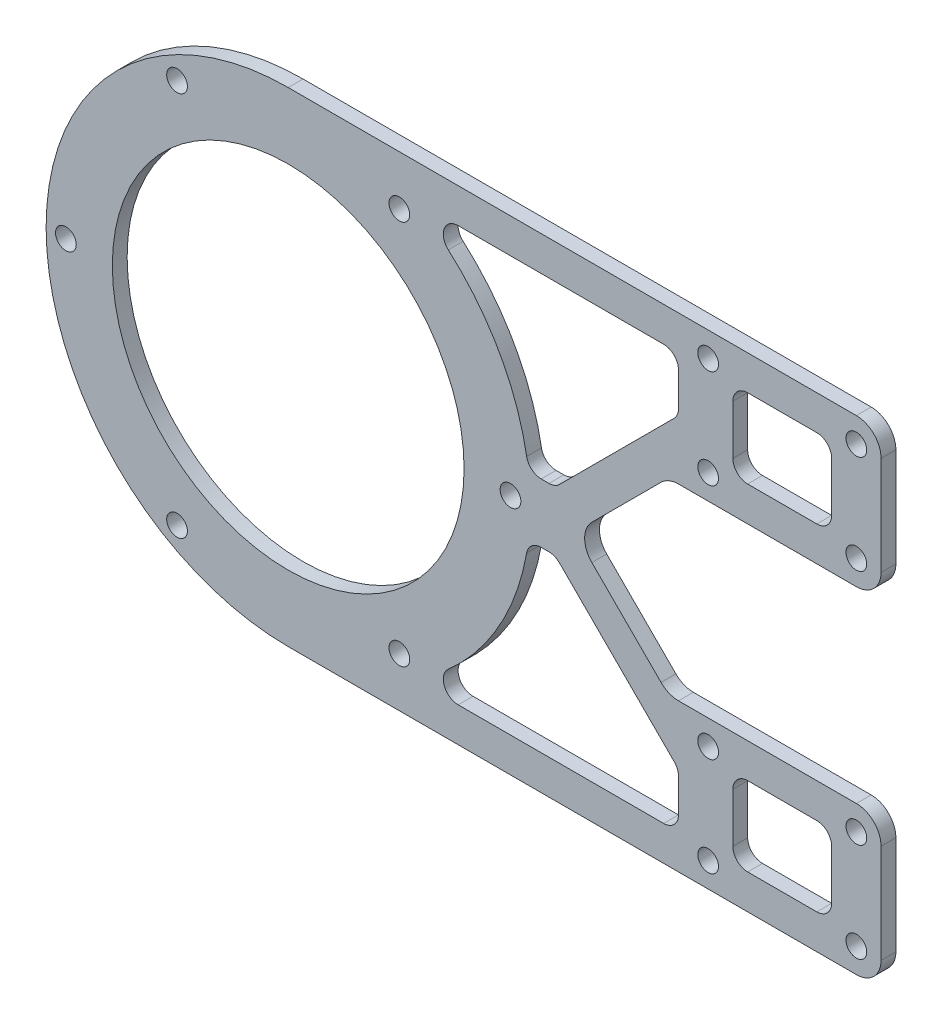
SolidWorks part; units mm, degrees
material "Thornel Mat VMA"
ref_plane "前视基准面" through (0, 0, 0) normal (0, 0, 1) x (1, 0, 0)
ref_plane "上视基准面" through (0, 0, 0) normal (0, 1, 0) x (1, 0, 0)
ref_plane "右视基准面" through (0, 0, 0) normal (1, 0, 0) x (0, 0, -1)
other "Configuration Table"
sketch "草图1" plane through (0, 0, 0) normal (0, 0, 1) x (1, 0, 0)
  line L0 (0, 49) -> (115, 49)
  line L1 (0, -49) -> (115, -49)
  line L2 (120, 44) -> (120, 24)
  line L3 (115, 19) -> (79, 19)
  line L4 (0, 0) -> (18.0163, 0) construction
  line L5 (115, -19) -> (79, -19)
  line L6 (120, -44) -> (120, -24)
  line L7 (75.4645, 17.5355) -> (61.4645, 3.5355)
  line L8 (75.4645, -17.5355) -> (61.4645, -3.5355)
  circle A0 centre (0, 0) radius 45 construction
  circle A1 centre (-45, 0) radius 2.1
  circle A2 centre (-22.5, 38.9711) radius 2.1
  circle A3 centre (22.5, 38.9711) radius 2.1
  circle A4 centre (45, 0) radius 2.1
  circle A5 centre (22.5, -38.9711) radius 2.1
  circle A6 centre (-22.5, -38.9711) radius 2.1
  circle A7 centre (0, 0) radius 35.6
  arc A8 (0, 49) -> (0, -49) centre (0, 0) ccw
  arc A9 (79, -19) -> (75.4645, -17.5355) centre (79, -14) cw
  arc A10 (79, 19) -> (75.4645, 17.5355) centre (79, 14) ccw
  arc A11 (61.4645, 3.5355) -> (61.4645, -3.5355) centre (65, 0) ccw
  arc A12 (115, -49) -> (120, -44) centre (115, -44) ccw
  arc A13 (115, -19) -> (120, -24) centre (115, -24) cw
  arc A14 (120, 24) -> (115, 19) centre (115, 24) cw
  arc A15 (115, 49) -> (120, 44) centre (115, 44) cw
  point P18 (0, 0)
  point P30 (76.9289, -19)
  point P33 (76.9289, 19)
  point P36 (57.9289, 0)
  point P39 (120, -49)
  point P42 (120, -19)
  point P45 (120, 19)
  point P48 (120, 49)
  dimension "D1" = 90
  dimension "D2" = 4.2
  dimension "D4" = 71.2
  dimension "D5" = 49
  dimension "D8" = 5
  dimension "D9" = 5
  dimension "D6" = 30
  dimension "D7" = 45
  dimension "D10" = 20
  dimension "D11" = 120
  dimension "D3" = 6
extrude "凸台-拉伸1" add sketch "草图1" along normal blind 3
sketch "草图2" plane through (0, 0, 0) normal (0, 0, 1) x (1, 0, 0)
  line L0 (120, 34) -> (97.6002, 34) construction
  line L2 (0, 0) -> (15.5153, 0) construction
  line L3 (120, 24) -> (120, 44) construction
  line L4 (85, -44) -> (115, -24) construction
  line L5 (85, 24) -> (115, 24) construction
  line L6 (85, 24) -> (85, 44) construction
  line L7 (85, 44) -> (115, 44) construction
  line L8 (115, 24) -> (115, 44) construction
  line L9 (85, 24) -> (115, 44) construction
  line L10 (85, 44) -> (115, 24) construction
  line L11 (85, -24) -> (115, -44) construction
  line L12 (115, -24) -> (115, -44) construction
  line L13 (85, -44) -> (115, -44) construction
  line L14 (85, -24) -> (85, -44) construction
  line L15 (85, -24) -> (115, -24) construction
  circle A0 centre (85, 44) radius 2.1
  circle A1 centre (115, 44) radius 2.1
  circle A3 centre (115, 24) radius 2.1
  circle A4 centre (85, 24) radius 2.1
  circle A5 centre (85, -24) radius 2.1
  circle A6 centre (115, -24) radius 2.1
  circle A7 centre (115, -44) radius 2.1
  circle A8 centre (85, -44) radius 2.1
  point P3 (120, 34)
  point P8 (100, 34)
  point P27 (100, -34)
  dimension "D1" = 4.2
  dimension "D2" = 4.2
  dimension "D3" = 30
  dimension "D4" = 20
  dimension "D5" = 5
extrude "切除-拉伸1" cut sketch "草图2" along normal blind 3
sketch "草图3" plane through (0, 0, 0) normal (0, 0, 1) x (1, 0, 0)
  line L0 (34.3948, 42) -> (76, 42)
  line L1 (79, 39) -> (79, 32.2132)
  line L2 (78.1213, 30.0919) -> (54.9081, 6.8787)
  line L3 (52.7868, 6) -> (51.2152, 6)
  line L4 (115, 49) -> (0, 49) construction
  line L5 (61.4645, 3.5355) -> (75.4645, 17.5355) construction
  line L13 (85, 44) -> (115, 24) construction
  line L14 (0, 0) -> (45, 0) construction
  line L15 (115, 44) -> (85, 24) construction
  line L22 (52.7868, -6) -> (51.2152, -6)
  line L23 (78.1213, -30.0919) -> (54.9081, -6.8787)
  line L24 (79, -39) -> (79, -32.2132)
  line L25 (34.3948, -42) -> (76, -42)
  line L26 (90, -42) -> (110, -26) construction
  line L27 (93, 26) -> (107, 26)
  line L28 (90, 29) -> (90, 39)
  line L29 (93, 42) -> (107, 42)
  line L30 (110, 29) -> (110, 39)
  line L31 (90, 26) -> (110, 42) construction
  line L32 (90, 42) -> (110, 26) construction
  line L33 (90, -26) -> (110, -42) construction
  line L34 (110, -29) -> (110, -39)
  line L35 (93, -42) -> (107, -42)
  line L36 (90, -29) -> (90, -39)
  line L37 (93, -26) -> (107, -26)
  arc A0 (32.4105, 36.75) -> (48.2605, 8.4808) centre (0, 0) cw
  arc A1 (51.2152, 6) -> (48.2605, 8.4808) centre (51.2152, 9) cw
  arc A2 (54.9081, 6.8787) -> (52.7868, 6) centre (52.7868, 9) cw
  arc A3 (79, 32.2132) -> (78.1213, 30.0919) centre (76, 32.2132) cw
  arc A4 (76, 42) -> (79, 39) centre (76, 39) cw
  arc A5 (34.3948, 42) -> (32.4105, 36.75) centre (34.3948, 39) ccw
  circle A6 centre (85, 44) radius 2.1 construction
  circle A7 centre (45, 0) radius 2.1 construction
  arc A21 (34.3948, -42) -> (32.4105, -36.75) centre (34.3948, -39) cw
  arc A22 (76, -42) -> (79, -39) centre (76, -39) ccw
  arc A23 (79, -32.2132) -> (78.1213, -30.0919) centre (76, -32.2132) ccw
  arc A24 (54.9081, -6.8787) -> (52.7868, -6) centre (52.7868, -9) ccw
  arc A25 (51.2152, -6) -> (48.2605, -8.4808) centre (51.2152, -9) ccw
  arc A26 (32.4105, -36.75) -> (48.2605, -8.4808) centre (0, 0) ccw
  circle A27 centre (115, 44) radius 2.1 construction
  arc A28 (93, 26) -> (90, 29) centre (93, 29) cw
  arc A29 (107, 26) -> (110, 29) centre (107, 29) ccw
  arc A30 (107, 42) -> (110, 39) centre (107, 39) cw
  arc A31 (90, 39) -> (93, 42) centre (93, 39) cw
  arc A32 (90, -39) -> (93, -42) centre (93, -39) ccw
  arc A33 (107, -42) -> (110, -39) centre (107, -39) ccw
  arc A34 (107, -26) -> (110, -29) centre (107, -29) cw
  arc A35 (93, -26) -> (90, -29) centre (93, -29) ccw
  point P29 (100, 34)
  point P68 (100, -34)
  dimension "D1" = 3
  dimension "D2" = 49
  dimension "D9" = 3
  dimension "D3" = 7
  dimension "D4" = 7
  dimension "D5" = 6
  dimension "D6" = 6
  dimension "D7" = 7
  dimension "D8" = 5
extrude "切除-拉伸2" cut sketch "草图3" along normal through all
